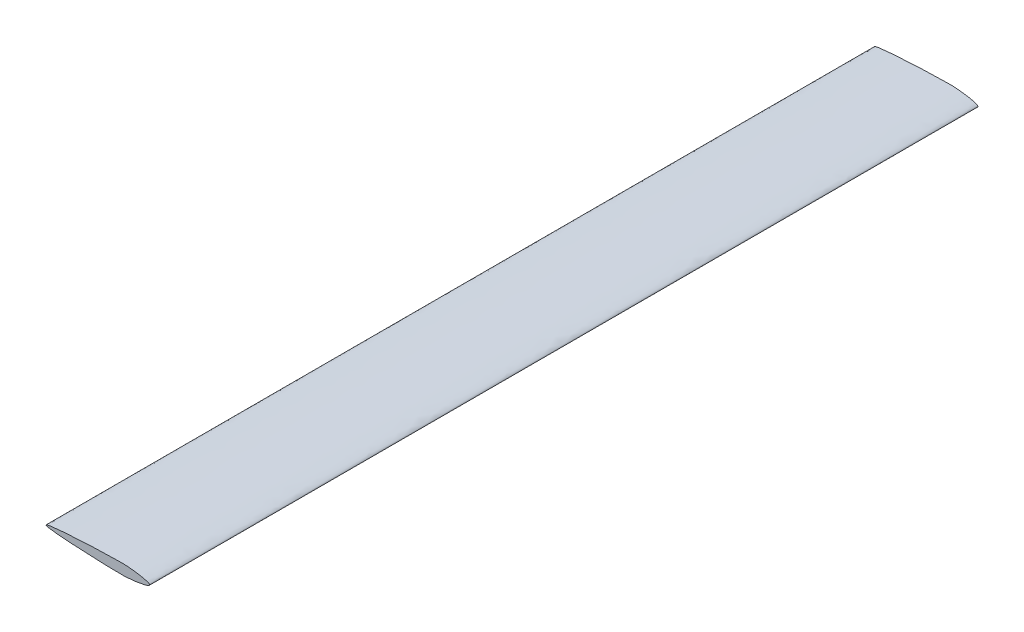
SolidWorks part; units mm, degrees
ref_plane "Front Plane" through (0, 0, 0) normal (0, 0, 1) x (1, 0, 0)
ref_plane "Top Plane" through (0, 0, 0) normal (0, 1, 0) x (1, 0, 0)
ref_plane "Right Plane" through (0, 0, 0) normal (1, 0, 0) x (0, 0, -1)
sketch "Sketch2" plane through (0, 0, 0) normal (0, 0, 1) x (1, 0, 0)
  line L0 (0, 0) -> (-762, 0) construction
  line L1 (-196.1364, -38.1) -> (-196.1364, 38.1) construction
  line L2 (-220.6894, -38.1) -> (-220.6894, 38.1) construction
  spline S0 degree 3 poles (-141.4492, -38.8842) (125.9693, 0) (-141.4492, 38.8842) (-384.4837, 36.5658) (-1123.1744, 0) (-384.4837, -36.5658) (-141.4492, -38.8842) (125.9693, 0) (-141.4492, 38.8842) knots -0.5 -0.146254 -0.130249 0 0.130249 0.146254 0.5 0.853746 0.869751 1 1.130249 1.146254 1.5 only from (0, 0) to (0, 0)
  point P6 (-196.1364, 0)
  point P8 (-220.6894, 0)
extrude "Boss-Extrude1" add sketch "Sketch2" along normal blind 6096
